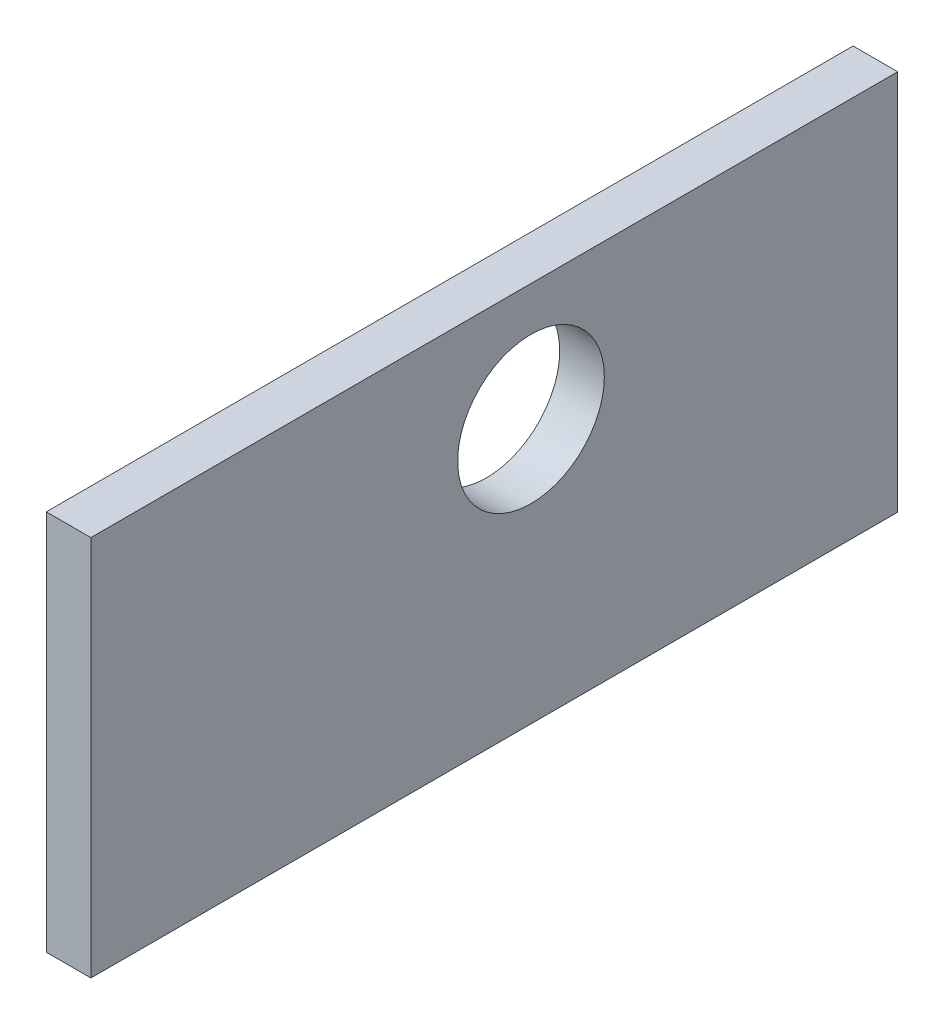
SolidWorks part; units mm, degrees
material "6061 Alloy"
ref_plane "Front Plane" through (0, 0, 0) normal (0, 0, 1) x (1, 0, 0)
ref_plane "Top Plane" through (0, 0, 0) normal (0, 1, 0) x (1, 0, 0)
ref_plane "Right Plane" through (0, 0, 0) normal (1, 0, 0) x (0, 0, -1)
sketch "Sketch1" plane through (0, 0, 0) normal (1, 0, 0) x (0, 0, -1)
  line L0 (0, -28.575) -> (0, 12.7) construction
  line L1 (-47.625, 12.7) -> (39.6875, 12.7)
  line L2 (-47.625, 12.7) -> (-47.625, -28.575)
  line L3 (-47.625, -28.575) -> (39.6875, -28.575)
  line L4 (39.6875, 12.7) -> (39.6875, -28.575)
  circle A0 centre (0, 0) radius 7.9375
  point P5 (0, 0)
  point P9 (0, 0)
  dimension "D3" = 15.875
  dimension "D1" = 39.6875
  dimension "D2" = 12.7
  dimension "D4" = 28.575
  dimension "D5" = 47.625
extrude "Boss-Extrude1" add sketch "Sketch1" along normal blind 4.826
